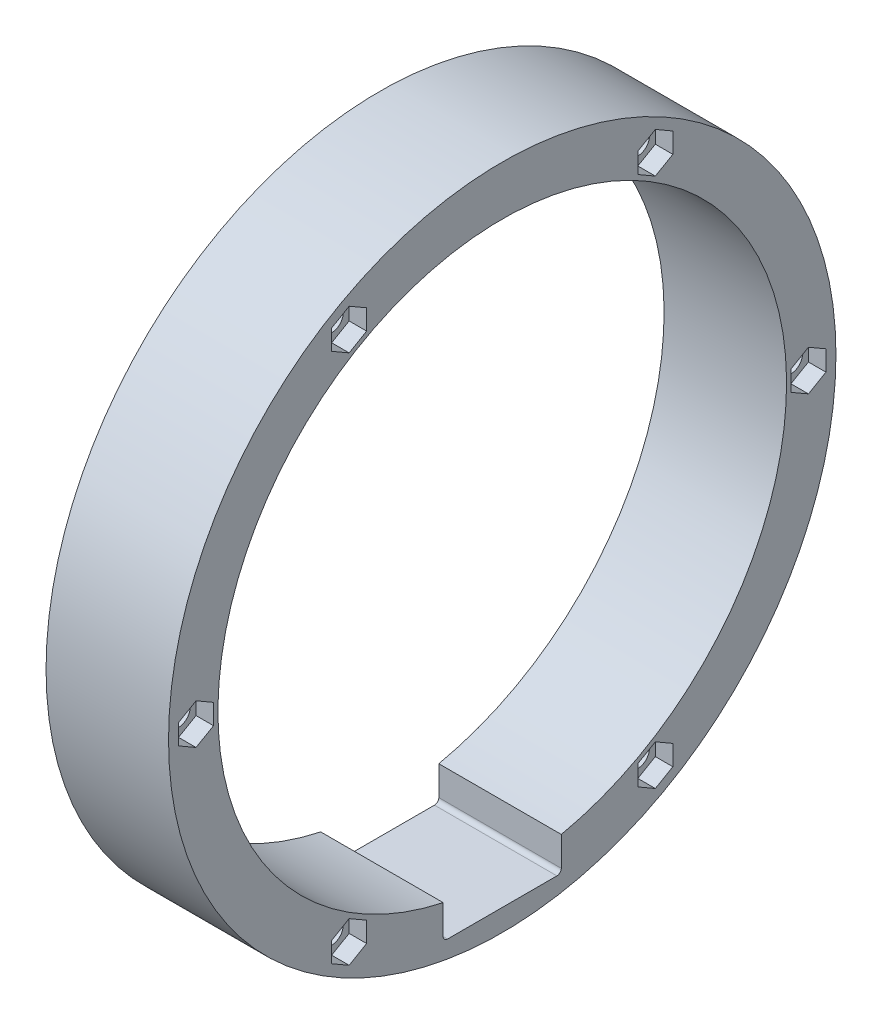
SolidWorks part; units mm, degrees
ref_plane "Front Plane" through (0, 0, 0) normal (0, 0, 1) x (1, 0, 0)
ref_plane "Top Plane" through (0, 0, 0) normal (0, 1, 0) x (1, 0, 0)
ref_plane "Right Plane" through (0, 0, 0) normal (1, 0, 0) x (0, 0, -1)
sketch "Sketch1" plane through (0, 0, 0) normal (1, 0, 0) x (0, 0, -1)
  circle A0 centre (0, 0) radius 76.29
  circle A1 centre (0, 0) radius 65
  dimension "D1" = 152.58
  dimension "D2" = 130
extrude "Boss-Extrude1" add sketch "Sketch1" along normal blind 28
sketch "Sketch2" plane through (28, 0, 0) normal (1, 0, 0) x (0, 0, -1)
  line L0 (0, -34.8517) -> (0, -97.703) construction
  line L1 (-13.5, -51.894) -> (13.5, -51.894)
  line L2 (-13.5, -51.894) -> (-13.5, -70.29)
  line L3 (-12.5, -71.29) -> (12.5, -71.29)
  line L4 (13.5, -51.894) -> (13.5, -70.29)
  circle A1 centre (0, 0) radius 76.29 construction
  arc A2 (-13.5, -70.29) -> (-12.5, -71.29) centre (-12.5, -70.29) ccw
  arc A3 (13.5, -70.29) -> (12.5, -71.29) centre (12.5, -70.29) cw
  point P6 (0, -51.894)
  point P10 (0, -76.29)
  dimension "D2" = 1
  dimension "D3" = 1
  dimension "D1" = 5
  dimension "D4" = 27
extrude "Cut-Extrude1" cut sketch "Sketch2" against normal up to next
sketch "Sketch3" plane through (28, 0, 0) normal (1, 0, 0) x (0, 0, -1)
  line L0 (-94.7404, 0) -> (95.285, 0) construction
  circle A0 centre (-70, 0) radius 2.65
  circle A1 centre (-35, 60.6218) radius 2.65
  circle A2 centre (35, 60.6218) radius 2.65
  circle A3 centre (70, 0) radius 2.65
  circle A4 centre (35, -60.6218) radius 2.65
  circle A5 centre (-35, -60.6218) radius 2.65
  point P17 (0, 0)
  dimension "D1" = 5.3
  dimension "D2" = 70
  dimension "D3" = 6
extrude "Cut-Extrude2" cut sketch "Sketch3" against normal up to next
sketch "Sketch4" plane through (28, 0, 0) normal (1, 0, 0) x (0, 0, -1)
  line L0 (-39, 58.3124) -> (-35, 56.003)
  line L1 (-70, -4.6188) -> (-66, -2.3094)
  line L2 (-66, -2.3094) -> (-66, 2.3094)
  line L3 (-66, 2.3094) -> (-70, 4.6188)
  line L4 (-70, 4.6188) -> (-74, 2.3094)
  line L5 (-74, 2.3094) -> (-74, -2.3094)
  line L6 (-74, -2.3094) -> (-70, -4.6188)
  line L7 (-35, 56.003) -> (-31, 58.3124)
  line L8 (-31, 58.3124) -> (-31, 62.9312)
  line L9 (-31, 62.9312) -> (-35, 65.2406)
  line L10 (-35, 65.2406) -> (-39, 62.9312)
  line L11 (-39, 62.9312) -> (-39, 58.3124)
  line L12 (31, 62.9312) -> (31, 58.3124)
  line L13 (31, 58.3124) -> (35, 56.003)
  line L14 (35, 56.003) -> (39, 58.3124)
  line L15 (39, 58.3124) -> (39, 62.9312)
  line L16 (39, 62.9312) -> (35, 65.2406)
  line L17 (35, 65.2406) -> (31, 62.9312)
  line L18 (70, 4.6188) -> (66, 2.3094)
  line L19 (66, 2.3094) -> (66, -2.3094)
  line L20 (66, -2.3094) -> (70, -4.6188)
  line L21 (70, -4.6188) -> (74, -2.3094)
  line L22 (74, -2.3094) -> (74, 2.3094)
  line L23 (74, 2.3094) -> (70, 4.6188)
  line L24 (39, -58.3124) -> (35, -56.003)
  line L25 (35, -56.003) -> (31, -58.3124)
  line L26 (31, -58.3124) -> (31, -62.9312)
  line L27 (31, -62.9312) -> (35, -65.2406)
  line L28 (35, -65.2406) -> (39, -62.9312)
  line L29 (39, -62.9312) -> (39, -58.3124)
  line L30 (-31, -62.9312) -> (-31, -58.3124)
  line L31 (-31, -58.3124) -> (-35, -56.003)
  line L32 (-35, -56.003) -> (-39, -58.3124)
  line L33 (-39, -58.3124) -> (-39, -62.9312)
  line L34 (-39, -62.9312) -> (-35, -65.2406)
  line L35 (-35, -65.2406) -> (-31, -62.9312)
  circle A0 centre (-70, 0) radius 4 construction
  circle A1 centre (-35, 60.6218) radius 4 construction
  circle A2 centre (35, 60.6218) radius 4 construction
  circle A3 centre (70, 0) radius 4 construction
  circle A4 centre (35, -60.6218) radius 4 construction
  circle A5 centre (-35, -60.6218) radius 4 construction
  point P52 (0, 0)
  dimension "D1" = 8
  dimension "D2" = 6
extrude "Cut-Extrude3" cut sketch "Sketch4" against normal blind 4
